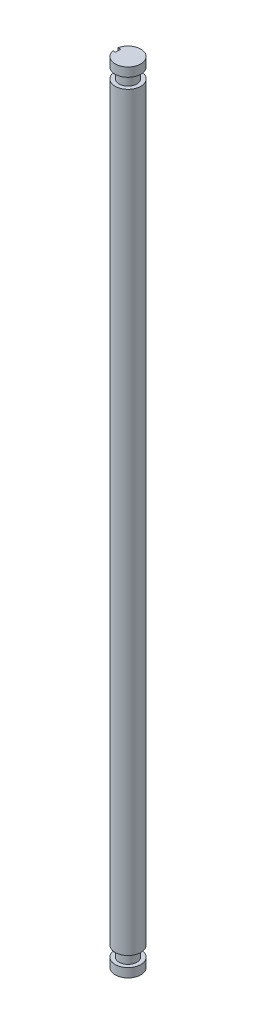
SolidWorks part; units mm, degrees
ref_plane "Front Plane" through (0, 0, 0) normal (1, 0, 0) x (0, 1, 0)
ref_plane "Top Plane" through (0, 0, 0) normal (0, 0, 1) x (0, 1, 0)
ref_plane "Right Plane" through (0, 0, 0) normal (0, 1, 0) x (-1, 0, 0)
sketch "Sketch1" plane through (0, 0, 0) normal (0, 0, 1) x (0, 1, 0)
  line L0 (-976.376, 0) -> (-976.376, 31.7309)
  line L1 (-976.376, 31.7309) -> (-954.024, 31.7309)
  line L2 (-954.024, 31.7309) -> (-954.024, 22.0218)
  line L3 (-954.024, 22.0218) -> (-928.2176, 22.0218)
  line L4 (-928.2176, 22.0218) -> (-928.2176, 31.7309)
  line L5 (-928.2176, 31.7309) -> (928.3446, 31.7309)
  line L6 (928.3446, 31.7309) -> (928.3446, 22.0218)
  line L7 (928.3446, 22.0218) -> (954.151, 22.0218)
  line L8 (954.151, 22.0218) -> (954.151, 31.7309)
  line L9 (954.151, 31.7309) -> (976.376, 31.7309)
  line L10 (976.376, 31.7309) -> (976.376, 0)
  line L11 (976.376, 0) -> (-976.376, 0)
  line L12 (-1001.776, 0) -> (1001.776, 0) construction
  point P14 (0, 0)
  dimension "D1" = 22.225
  dimension "D2" = 48.0314
  dimension "D3" = 1904.5936
  dimension "D4" = 1930.4
  dimension "D5" = 1952.752
  dimension "D6" = 9.7092
  dimension "D7" = 31.7309
revolve "Revolve1" add sketch "Sketch1" angle 360 about L12
sketch "Sketch2" plane through (0, 0, 0) normal (0, 1, 0) x (-1, 0, 0)
  line L1 (24.6062, -6.35) -> (88.0682, -6.35)
  line L2 (24.6062, -6.35) -> (24.6062, 6.35)
  line L3 (24.6062, 6.35) -> (88.0682, 6.35)
  line L4 (88.0682, -6.35) -> (88.0682, 6.35)
  point P2 (0, 0)
  dimension "D1" = 63.4619
  dimension "D2" = 12.7
  dimension "D3" = 88.0682
  dimension "D4" = 6.35
extrude "Cut-Extrude2" cut sketch "Sketch2" along normal blind 1997.456 from offset 998.728
